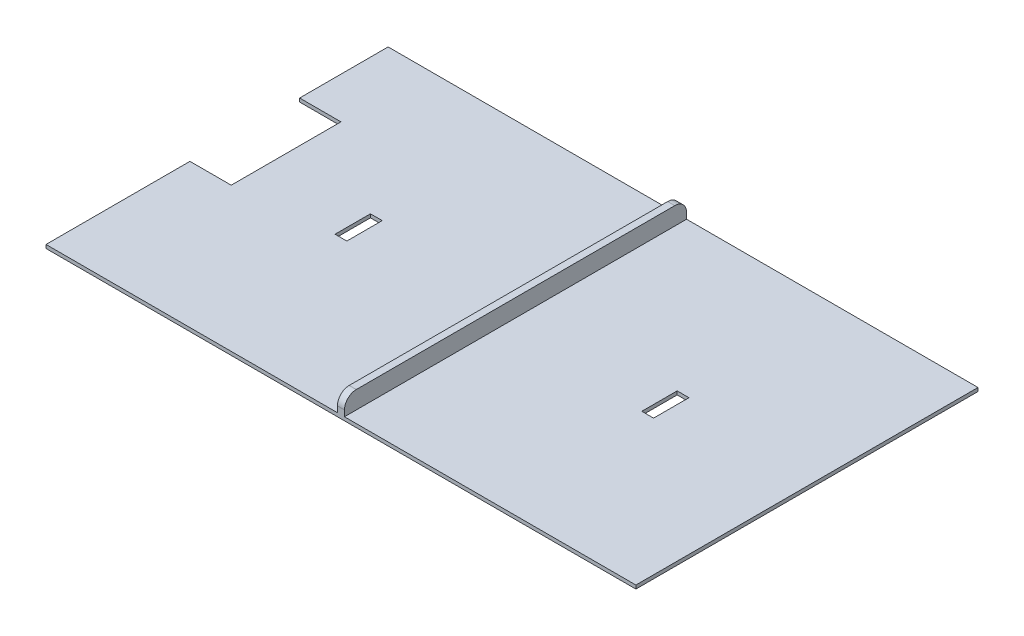
SolidWorks part; units mm, degrees
ref_plane "Front Plane" through (0, 0, 0) normal (0, 0, 1) x (1, 0, 0)
ref_plane "Top Plane" through (0, 0, 0) normal (0, 1, 0) x (1, 0, 0)
ref_plane "Right Plane" through (0, 0, 0) normal (1, 0, 0) x (0, 0, -1)
sketch "Sketch1" plane through (0, 0, 0) normal (0, 1, 0) x (1, 0, 0)
  line L0 (-250, 145) -> (-250, 70) construction
  line L1 (-250, -145) -> (250, -145)
  line L2 (-250, -145) -> (-250, -23)
  line L3 (-250, 145) -> (250, 145)
  line L4 (250, -145) -> (250, 145)
  line L5 (-250, -145) -> (250, 145) construction
  line L6 (-250, 145) -> (250, -145) construction
  line L7 (-250, 70) -> (-215, 70)
  line L8 (-215, 70) -> (-215, -23)
  line L9 (-215, -23) -> (-250, -23)
  line L10 (-250, 70) -> (-250, 145)
  point P0 (0, 0)
  point P7 (-232.5, -23)
  dimension "D1" = 290
  dimension "D2" = 500
  dimension "D3" = 93
  dimension "D4" = 35
  dimension "D5" = 168
  dimension "D6" = 75
extrude "Boss-Extrude1" add sketch "Sketch1" along normal blind 3
sketch "Sketch2" plane through (0, 3, 0) normal (0, 1, 0) x (1, 0, 0)
  line L0 (-130, 0) -> (130, 0) construction
  line L2 (125, -15) -> (135, -15)
  line L3 (125, -15) -> (125, 15)
  line L4 (125, 15) -> (135, 15)
  line L5 (135, -15) -> (135, 15)
  line L6 (125, -15) -> (135, 15) construction
  line L7 (125, 15) -> (135, -15) construction
  line L8 (-135, -15) -> (-125, -15)
  line L9 (-135, -15) -> (-135, 15)
  line L10 (-135, 15) -> (-125, 15)
  line L11 (-125, -15) -> (-125, 15)
  line L12 (-135, -15) -> (-125, 15) construction
  line L13 (-135, 15) -> (-125, -15) construction
  point P4 (0, 0)
  dimension "D1" = 260
  dimension "D2" = 30
  dimension "D3" = 30
  dimension "D4" = 10
  dimension "D5" = 10
extrude "Cut-Extrude1" cut sketch "Sketch2" against normal up to surface (3 mm away) up to face at (-116.25, 0, -11.75)
sketch "Sketch3" plane through (0, 3, 0) normal (0, 1, 0) x (1, 0, 0)
  line L0 (-250, -145) -> (250, -145) construction
  line L1 (-3, 145) -> (3, 145)
  line L2 (-3, 145) -> (-3, -145)
  line L3 (-3, -145) -> (3, -145)
  line L4 (3, 145) -> (3, -145)
  line L5 (-3, 145) -> (3, -145) construction
  line L6 (-3, -145) -> (3, 145) construction
  point P0 (0, 0)
  dimension "D1" = 6
extrude "Boss-Extrude2" add sketch "Sketch3" along normal blind 15
fillet "Fillet1" radius 10 2 edges at (0, 18, -145) (0, 18, 145)
